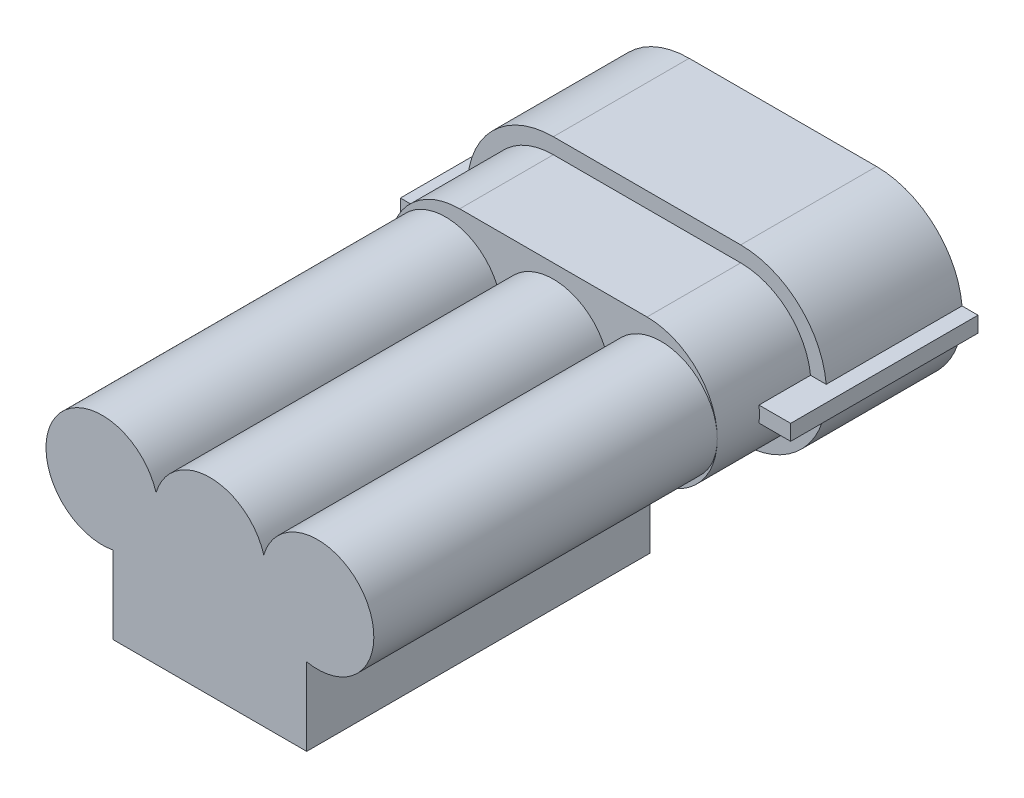
SolidWorks part; units mm, degrees
ref_plane "正面" through (0, 0, 0) normal (0, 0, 1) x (1, 0, 0)
ref_plane "平面" through (0, 0, 0) normal (0, 1, 0) x (1, 0, 0)
ref_plane "右側面" through (0, 0, 0) normal (1, 0, 0) x (0, 0, -1)
sketch "ｽｹｯﾁ1" plane through (0, 0, 0) normal (0, 0, 1) x (1, 0, 0)
  line L0 (-6, 0) -> (6, 0) construction
  line L1 (-6, 5.5) -> (6, 5.5)
  line L2 (-6, -5.5) -> (6, -5.5)
  arc A0 (-6, 5.5) -> (-6, -5.5) centre (-6, 0) ccw
  arc A1 (6, -5.5) -> (6, 5.5) centre (6, 0) ccw
  point P2 (0, 0)
  point P7 (-11.5, 0)
  point P8 (11.5, 0)
  point P10 (0, 0)
  point P11 (0, 0)
  dimension "D1" = 23
  dimension "D2" = 11
extrude "ﾎﾞｽ - 押し出し1" add sketch "ｽｹｯﾁ1" along normal blind 8.7
sketch "ｽｹｯﾁ4" plane through (0, 0, 8.7) normal (0, 0, 1) x (1, 0, 0)
  line L4 (-6, -4.5) -> (6, -4.5)
  line L5 (6, 4.5) -> (-6, 4.5)
  line L6 (-6, -4.5) -> (6, -4.5)
  line L7 (6, 4.5) -> (-6, 4.5)
  arc A4 (-6, 4.5) -> (-6, -4.5) centre (-6, 0) ccw
  arc A5 (6, -4.5) -> (6, 4.5) centre (6, 0) ccw
  arc A6 (-6, 4.5) -> (-6, -4.5) centre (-6, 0) ccw
  arc A7 (6, -4.5) -> (6, 4.5) centre (6, 0) ccw
  dimension "D1" = 1
extrude "ﾎﾞｽ - 押し出し2" add sketch "ｽｹｯﾁ4" along normal blind 6
sketch "ｽｹｯﾁ5" plane through (0, 0, 14.7) normal (0, 0, 1) x (1, 0, 0)
  line L0 (-10.5, 0) -> (10.5, 0) construction
  arc A0 (-3.45, 1.0283) -> (-3.45, -1.0283) centre (-6.9, 0) ccw
  arc A2 (3.45, -1.0283) -> (3.45, 1.0283) centre (6.9, 0) ccw
  arc A3 (-6, 4.5) -> (-6, -4.5) centre (-6, 0) ccw construction
  arc A4 (3.45, 1.0283) -> (-3.45, 1.0283) centre (0, 0) ccw
  arc A7 (6, -4.5) -> (6, 4.5) centre (6, 0) ccw construction
  arc A8 (-3.45, -1.0283) -> (3.45, -1.0283) centre (0, 0) ccw
  point P3 (4.1793, 0)
  point P6 (-5.4721, -1.2807)
  point P17 (-10.5, 0)
  point P19 (10.5, 0)
  point P20 (10.5, 0)
  dimension "D1" = 7.2
extrude "ﾎﾞｽ - 押し出し7" add sketch "ｽｹｯﾁ5" along normal blind 22
sketch "ｽｹｯﾁ6" plane through (0, -5.5, 0) normal (0, -1, 0) x (1, 0, 0)
  line L1 (-6.2, 36.7) -> (6.2, 36.7)
  line L2 (-6.2, 36.7) -> (-6.2, 0)
  line L3 (-6.2, 0) -> (6.2, 0)
  line L4 (6.2, 36.7) -> (6.2, 0)
  line L5 (-6.2, 36.7) -> (6.2, 0) construction
  line L6 (-6.2, 0) -> (6.2, 36.7) construction
  line L8 (0, 36.7) -> (0, 0) construction
  line L11 (3.45, 36.7) -> (-3.45, 36.7) construction
  point P0 (0, 18.35)
  dimension "D1" = 12.4
extrude "ﾎﾞｽ - 押し出し15" add sketch "ｽｹｯﾁ6" against normal up to body separate body
ref_plane "平面2" through (12.5, 0, 0) normal (1, 0, 0) x (0, 0, -1)
sketch "ｽｹｯﾁ10" plane through (12.5, 0, 0) normal (1, 0, 0) x (0, 0, -1)
  line L1 (0, -0.5) -> (-12, -0.5)
  line L2 (0, -0.5) -> (0, 0.5)
  line L3 (0, 0.5) -> (-12, 0.5)
  line L4 (-12, -0.5) -> (-12, 0.5)
  line L5 (0, 0) -> (-37.3464, 0) construction
  line L6 (0, -5.4964) -> (0, 5.5) construction
  dimension "D1" = 12
  dimension "D2" = 1
extrude "ﾎﾞｽ - 押し出し16" add sketch "ｽｹｯﾁ10" against normal up to body separate body
mirror "ﾐﾗｰ1" about plane through (0, 0, 0) normal (1, 0, 0) of "ﾎﾞｽ - 押し出し16"
sketch "ｽｹｯﾁ11" plane through (0, -5.5, 0) normal (0, -1, 0) x (1, 0, 0)
  line L0 (6.2, 36.7) -> (-6.2, 36.7) construction
  line L1 (6.2, 36.7) -> (-6.2, 36.7)
  line L2 (6.2, 36.7) -> (6.2, 14.7)
  line L3 (6.2, 14.7) -> (-6.2, 14.7)
  line L4 (-6.2, 36.7) -> (-6.2, 14.7)
  line L5 (6.2, 0) -> (6.2, 36.7) construction
  line L6 (-6.2, 36.7) -> (-6.2, 0) construction
  dimension "D1" = 22
extrude "ﾎﾞｽ - 押し出し17" add sketch "ｽｹｯﾁ11" along normal blind 3
